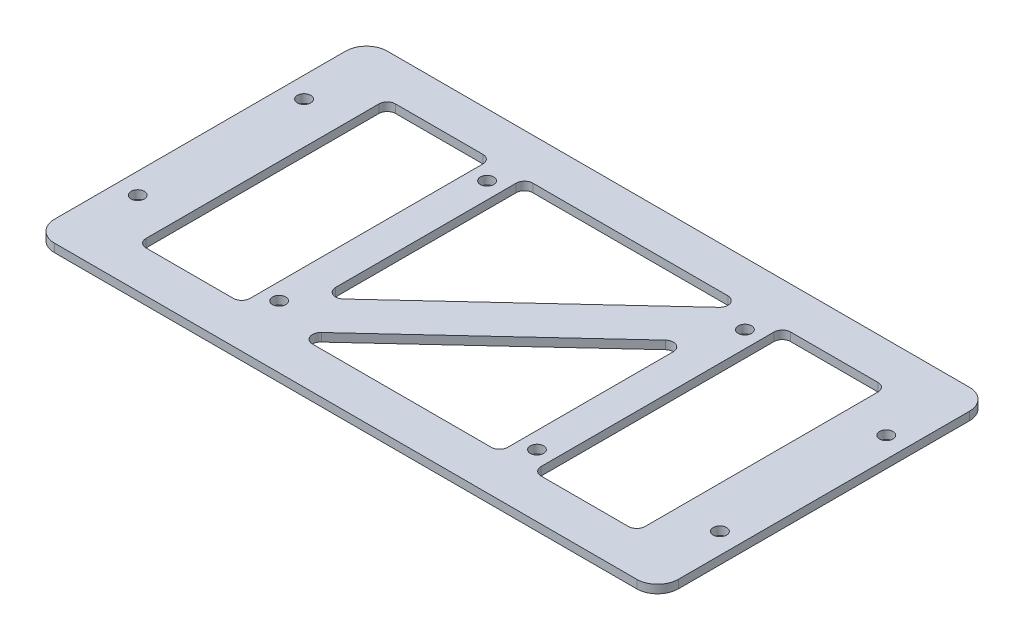
SolidWorks part; units mm, degrees
material "环氧树脂FR-4"
ref_plane "前视基准面" through (0, 0, 0) normal (0, 0, 1) x (1, 0, 0)
ref_plane "上视基准面" through (0, 0, 0) normal (0, 1, 0) x (1, 0, 0)
ref_plane "右视基准面" through (0, 0, 0) normal (1, 0, 0) x (0, 0, -1)
sketch "草图1" plane through (0, 0, 0) normal (0, 1, 0) x (1, 0, 0)
  line L1 (-75, 40) -> (75, 40)
  line L2 (-75, 40) -> (-75, -40)
  line L3 (-75, -40) -> (75, -40)
  line L4 (75, 40) -> (75, -40)
  line L5 (-75, 40) -> (75, -40) construction
  line L6 (-75, -40) -> (75, 40) construction
  point P0 (0, 0)
  dimension "D1" = 80
  dimension "D2" = 150
extrude "凸台-拉伸1" add sketch "草图1" along normal blind 2
sketch "草图2" plane through (0, 2, 0) normal (0, 1, 0) x (1, 0, 0)
  line L0 (0, -1.1) -> (0, 1.1) construction
  line L1 (-1.1, 0) -> (1.1, 0) construction
  line L2 (-75, 40) -> (-75, -40) construction
  point P0 (-31, 25)
  point P4 (31, 25)
  point P7 (31, -25)
  point P8 (-31, -25)
  point P9 (-70, 20)
  point P10 (-70, -20)
  point P13 (70, -20)
  point P14 (70, 20)
  dimension "D1" = 25
  dimension "D2" = 31
  dimension "D3" = 5
  dimension "D4" = 20
hole_wizard "Ø3.2 (3.2) 直径孔1" positions "3D草图1" profile "草图3" hole size "Ø3.2" standard "GB" end condition through all
sketch3d "3D草图1"
  point P0 (-31, 2, -25)
  point P3 (-31, 2, 25)
  point P6 (31, 2, 25)
  point P9 (31, 2, -25)
  point P12 (-70, 2, -20)
  point P15 (-70, 2, 20)
  point P18 (70, 2, 20)
  point P21 (70, 2, -20)
sketch "草图3" plane through (-31, 2, -25) normal (1, 0, 0) x (0, 0, 1)
  line L0 (0, 0) -> (0, 2)
  line L1 (0, 2) -> (1.6, 2)
  line L2 (1.6, 2) -> (1.6, 0)
  line L5 (1.6, 0) -> (0, 0)
  line L11 (0, -6.35) -> (0, 107.95) construction
  dimension "通孔孔直径" = 3.2
  dimension "通孔孔深度" = 2
sketch "草图4" plane through (0, 2, 0) normal (0, 1, 0) x (1, 0, 0)
  line L0 (-75, 40) -> (-75, -40) construction
  line L1 (-60, 30) -> (-35, 30)
  line L2 (-60, 30) -> (-60, -30)
  line L3 (-60, -30) -> (-35, -30)
  line L4 (-35, 30) -> (-35, -30)
  line L5 (75, 40) -> (-75, 40) construction
  line L6 (-75, -40) -> (75, -40) construction
  line L7 (-27, 30) -> (-27, -20)
  line L8 (-27, -20) -> (27, 30)
  line L9 (27, 30) -> (-27, 30)
  line L10 (-23.0813, -30) -> (27, -30)
  line L11 (27, -30) -> (27, 16.3716)
  line L12 (27, 16.3716) -> (-23.0813, -30)
  line L13 (0, -1.1) -> (0, 1.1) construction
  line L14 (60, -30) -> (35, -30)
  line L15 (35, 30) -> (35, -30)
  line L16 (60, 30) -> (35, 30)
  line L17 (60, 30) -> (60, -30)
  dimension "D1" = 15
  dimension "D2" = 10
  dimension "D3" = 10
  dimension "D4" = 4
  dimension "D5" = 50
  dimension "D6" = 4
  dimension "D7" = 10
  dimension "D8" = 8
  dimension "D9" = 10
  dimension "D10" = 0
  dimension "D11" = 10
fillet "圆角1" radius 5 4 edges at (75, 1, -40) (75, 1, 40) (-75, 1, 40) (-75, 1, -40)
extrude "切除-拉伸1" cut sketch "草图4" against normal through all
fillet "圆角2" radius 2 14 edges at (60, 1, 30) (60, 1, -30) (35, 1, -30) (35, 1, 30) (27, 1, 30) (-23.0813, 1, 30) (27, 1, -16.3716) (27, 1, -30) (-27, 1, -30) (-27, 1, 20) (-35, 1, 30) (-60, 1, 30) (-35, 1, -30) (-60, 1, -30)
